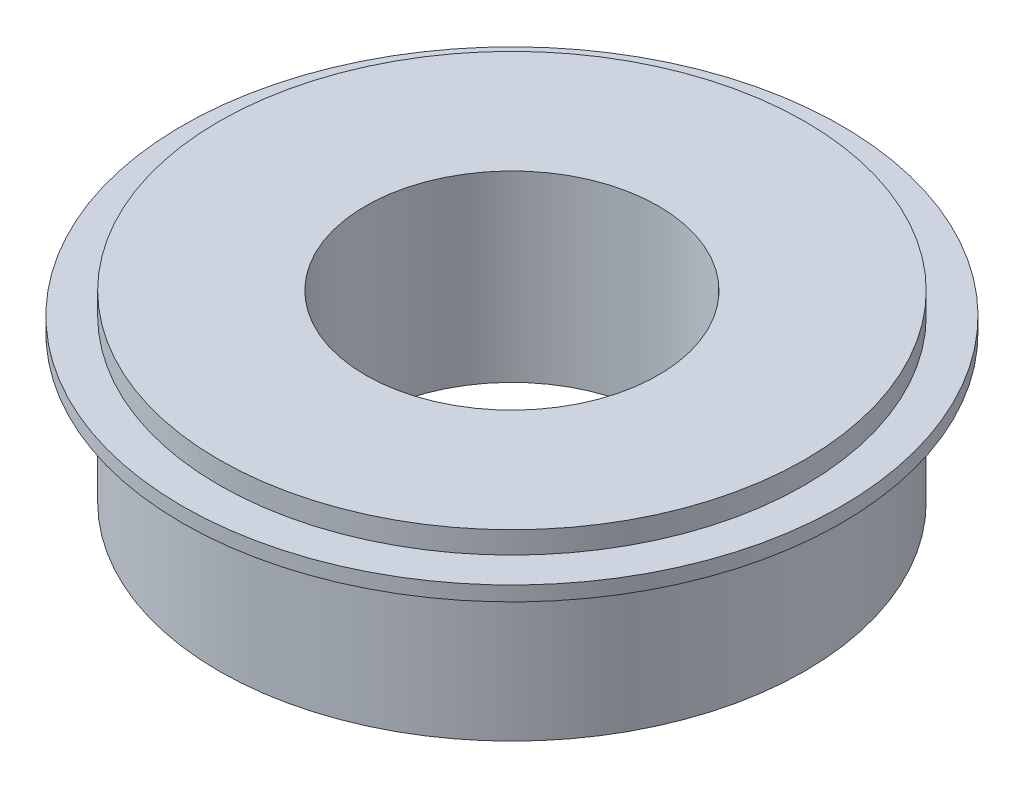
SolidWorks part; units mm, degrees
ref_plane "Front Plane" through (0, 0, 0) normal (0, 0, 1) x (1, 0, 0)
ref_plane "Top Plane" through (0, 0, 0) normal (0, 1, 0) x (1, 0, 0)
ref_plane "Right Plane" through (0, 0, 0) normal (1, 0, 0) x (0, 0, -1)
sketch "Sketch1" plane through (0, 0, 0) normal (0, 1, 0) x (1, 0, 0)
  circle A0 centre (0, 0) radius 8
  circle A1 centre (0, 0) radius 4
  dimension "D1" = 16
  dimension "D2" = 8
extrude "Boss-Extrude1" add sketch "Sketch1" along normal blind 5
sketch "Sketch2" plane through (0, 5, 0) normal (0, 1, 0) x (1, 0, 0)
  circle A0 centre (0, 0) radius 9
  circle A1 centre (0, 0) radius 8 construction
  circle A2 centre (0, 0) radius 8
  dimension "D1" = 18
extrude "Boss-Extrude2" add sketch "Sketch2" against normal blind 0.4 from offset 0.6 offset against normal yes
